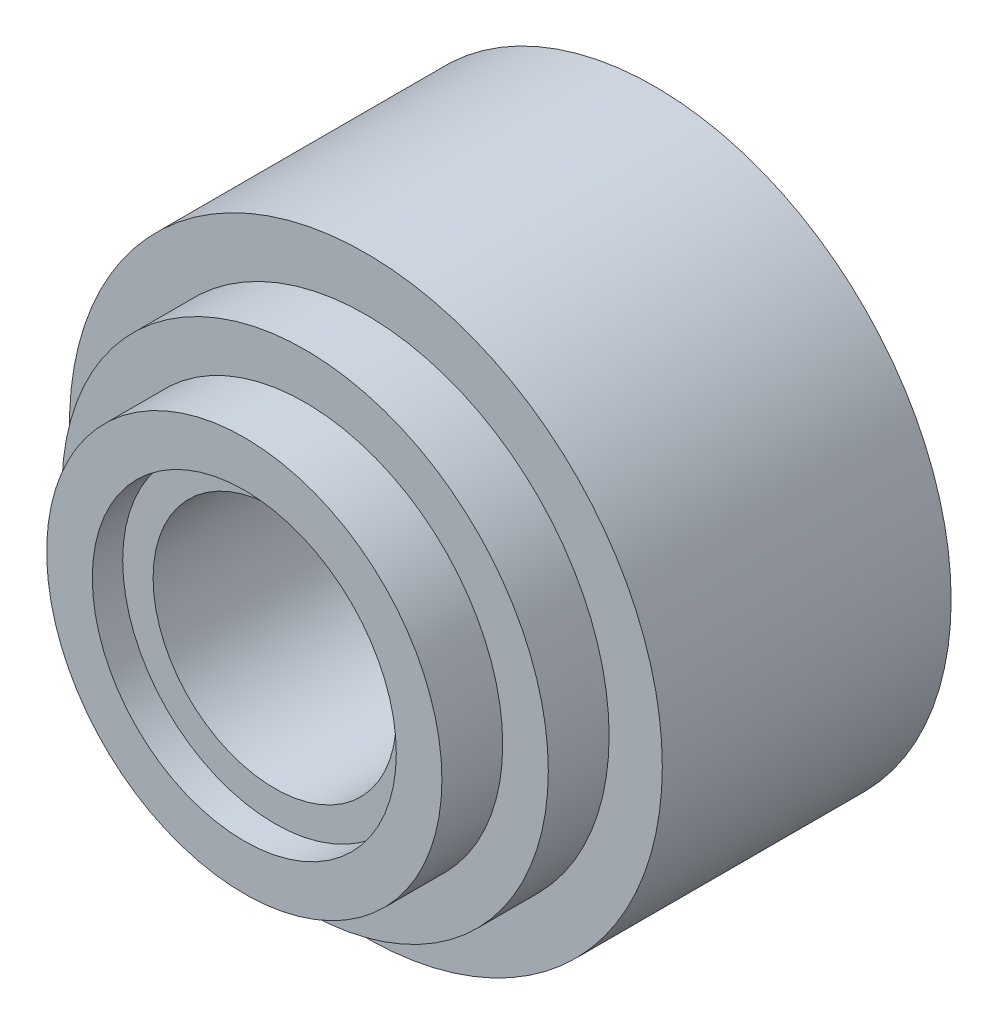
SolidWorks part; units mm, degrees
ref_plane "정면" through (0, 0, 0) normal (0, 0, 1) x (1, 0, 0)
ref_plane "윗면" through (0, 0, 0) normal (0, 1, 0) x (1, 0, 0)
ref_plane "우측면" through (0, 0, 0) normal (1, 0, 0) x (0, 0, -1)
sketch "스케치1" plane through (0, 0, 0) normal (0, 0, 1) x (1, 0, 0)
  circle A0 centre (0, 0) radius 9.75
  dimension "D1" = 19.5
extrude "돌출1" add sketch "스케치1" along normal blind 9.5
sketch "스케치2" plane through (0, 0, 9.5) normal (0, 0, 1) x (1, 0, 0)
  circle A0 centre (0, 0) radius 8
extrude "돌출2" add sketch "스케치2" along normal blind 2
sketch "스케치3" plane through (0, 0, 11.5) normal (0, 0, 1) x (1, 0, 0)
  circle A0 centre (0, 0) radius 6.5
extrude "돌출3" add sketch "스케치3" along normal blind 2
sketch "스케치4" plane through (0, 0, 0) normal (0, 0, -1) x (-1, 0, 0)
  circle A0 centre (0, 0) radius 4
extrude "컷-돌출1" cut sketch "스케치4" against normal through all
sketch "스케치5" plane through (0, 0, 0) normal (0, 0, -1) x (-1, 0, 0)
  circle A0 centre (0, 0) radius 5
extrude "컷-돌출2" cut sketch "스케치5" against normal blind 4
sketch "스케치6" plane through (0, 0, 13.5) normal (0, 0, 1) x (1, 0, 0)
  circle A0 centre (0, 0) radius 5
extrude "컷-돌출3" cut sketch "스케치6" against normal blind 1
